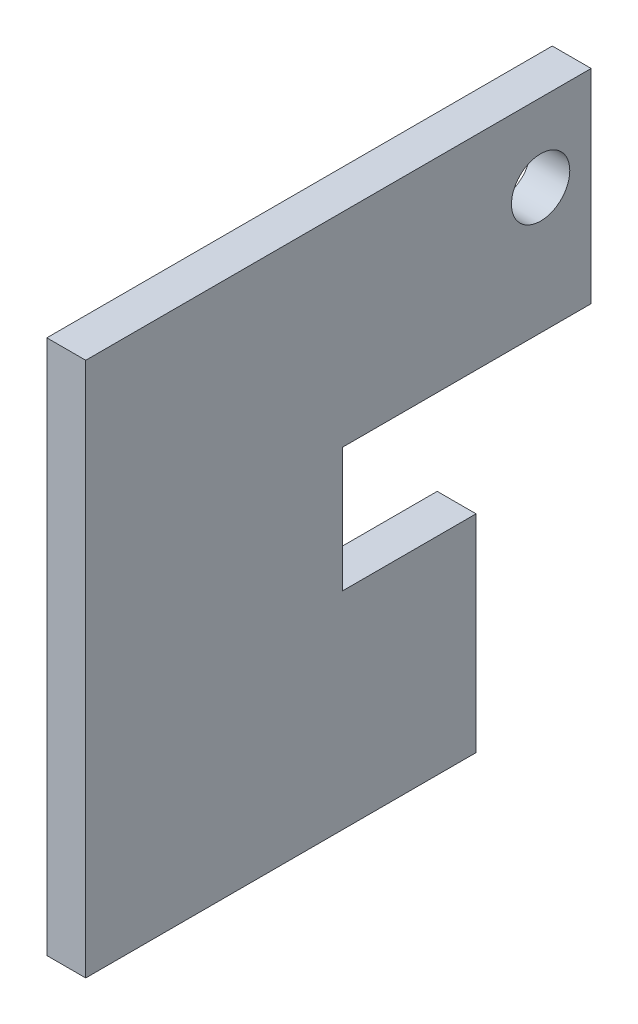
SolidWorks part; units mm, degrees
ref_plane "Front Plane" through (0, 0, 0) normal (0, 0, 1) x (1, 0, 0)
ref_plane "Top Plane" through (0, 0, 0) normal (0, 1, 0) x (1, 0, 0)
ref_plane "Right Plane" through (0, 0, 0) normal (1, 0, 0) x (0, 0, -1)
sketch "Sketch1" plane through (0, 0, 0) normal (1, 0, 0) x (0, 0, -1)
  line L1 (-16.51, 17.4752) -> (0, 17.4752)
  line L2 (-16.51, 17.4752) -> (-16.51, 0)
  line L3 (-16.51, 0) -> (0, 0)
  line L4 (0, 17.4752) -> (0, 0)
  dimension "D1" = 16.51
  dimension "D2" = 17.4752
extrude "Boss-Extrude1" add sketch "Sketch1" along normal blind 1.27
sketch "Sketch2" plane through (1.27, 0, 0) normal (1, 0, 0) x (0, 0, -1)
  line L0 (0, 17.4752) -> (-16.51, 17.4752) construction
  line L1 (0, 0) -> (0, 17.4752) construction
  circle A0 centre (-1.651, 14.9352) radius 0.9525
  dimension "D1" = 1.905
  dimension "D3" = 1.651
  dimension "D2" = 2.54
extrude "Cut-Extrude1" cut sketch "Sketch2" against normal through all
sketch "Sketch4" plane through (0, 0, 0) normal (0, 0, -1) x (-1, 0, 0)
  line L0 (0, 0) -> (0, 17.4752) construction
  line L1 (-1.27, 0) -> (0, 0)
  line L2 (-1.27, 0) -> (-1.27, 10.8204)
  line L3 (-1.27, 10.8204) -> (0, 10.8204)
  line L4 (0, 0) -> (0, 10.8204)
  dimension "D1" = 10.8204
extrude "Cut-Extrude2" cut sketch "Sketch4" against normal blind 3.7592 contours L3 L4 L1 L2
sketch "Sketch5" plane through (0, 0, 3.7592) normal (0, 0, -1) x (-1, 0, 0)
  line L0 (0, 0) -> (0, 10.8204) construction
  line L1 (-1.27, 10.8204) -> (0, 10.8204)
  line L2 (-1.27, 10.8204) -> (-1.27, 6.7564)
  line L3 (-1.27, 6.7564) -> (0, 6.7564)
  line L4 (0, 10.8204) -> (0, 6.7564)
  dimension "D1" = 4.064
extrude "Cut-Extrude3" cut sketch "Sketch5" against normal blind 4.3688
